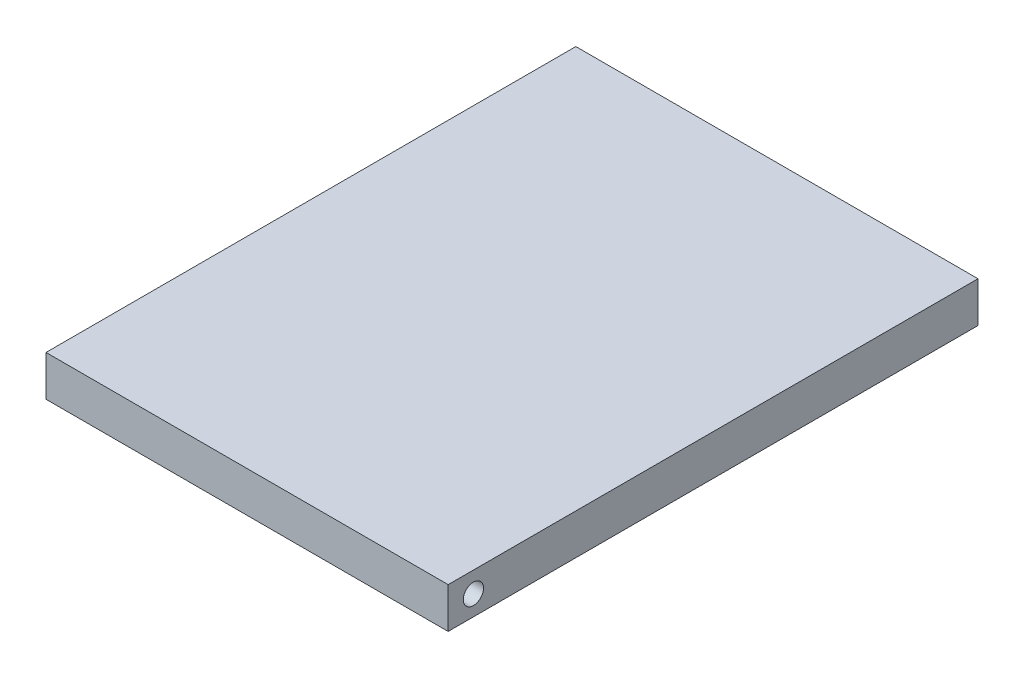
SolidWorks part; units mm, degrees
ref_plane "Front Plane" through (0, 0, 0) normal (0, 0, 1) x (1, 0, 0)
ref_plane "Top Plane" through (0, 0, 0) normal (0, 1, 0) x (1, 0, 0)
ref_plane "Right Plane" through (0, 0, 0) normal (1, 0, 0) x (0, 0, -1)
sketch "Sketch1" plane through (0, 0, 0) normal (0, 1, 0) x (1, 0, 0)
  line L1 (14.8738, -19.5957) -> (-14.8738, -19.5957)
  line L2 (14.8738, -19.5957) -> (14.8738, 19.5957)
  line L3 (14.8738, 19.5957) -> (-14.8738, 19.5957)
  line L4 (-14.8738, -19.5957) -> (-14.8738, 19.5957)
  line L5 (14.8738, -19.5957) -> (-14.8738, 19.5957) construction
  line L6 (14.8738, 19.5957) -> (-14.8738, -19.5957) construction
  line L7 (-14.8738, 19.5957) -> (14.8738, 19.5957)
  line L12 (-14.8738, 19.5957) -> (-14.8738, -19.5957)
  point P0 (0, 0)
  dimension "D1" = 29.7476
  dimension "D2" = 39.1913
extrude "Boss-Extrude1" add sketch "Sketch1" along normal blind 3 contours L2 L1 L4 L3
sketch "Sketch2" plane through (14.8738, 0, 0) normal (1, 0, 0) x (0, 0, -1)
  circle A0 centre (-17.7278, 1.4768) radius 0.75
  dimension "D1" = 1.5
extrude "Cut-Extrude1" cut sketch "Sketch2" against normal blind 13
